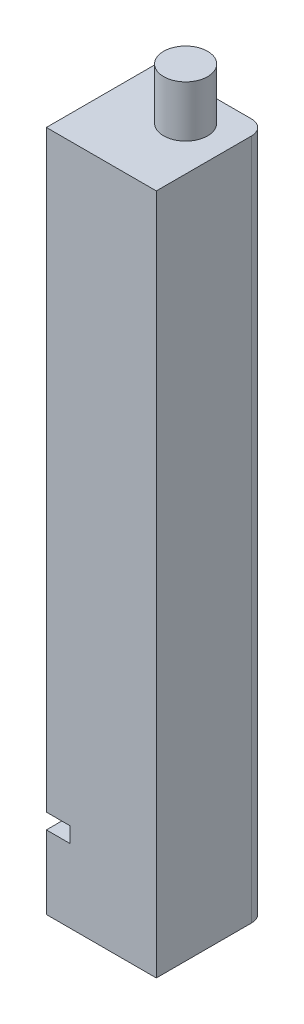
SolidWorks part; units mm, degrees
ref_plane "Front Plane" through (0, 0, 0) normal (0, 0, 1) x (1, 0, 0)
ref_plane "Top Plane" through (0, 0, 0) normal (0, 1, 0) x (1, 0, 0)
ref_plane "Right Plane" through (0, 0, 0) normal (1, 0, 0) x (0, 0, -1)
sketch "Sketch1" plane through (0, 0, 0) normal (0, 1, 0) x (1, 0, 0)
  line L0 (-68.486, 0) -> (57.6746, 0) construction
  line L1 (0, 62.7099) -> (0, -58.019) construction
  line L3 (-7.5, -7.5) -> (7.5, -7.5)
  line L4 (-7.5, -7.5) -> (-7.5, 7.5)
  line L5 (-7.5, 7.5) -> (7.5, 7.5)
  line L6 (7.5, -7.5) -> (7.5, 7.5)
  line L7 (-7.5, -7.5) -> (7.5, 7.5) construction
  line L8 (-7.5, 7.5) -> (7.5, -7.5) construction
  point P5 (0, 0)
  dimension "D1" = 15
  dimension "D2" = 15
extrude "Boss-Extrude1" add sketch "Sketch1" along normal blind 93
sketch "Sketch2" plane through (0, 93, 0) normal (0, 1, 0) x (1, 0, 0)
  line L0 (7.5, -7.5) -> (7.5, 7.5) construction
  line L2 (7.5, 7.5) -> (-7.5, 7.5) construction
  circle A0 centre (1.5, 2.5) radius 3
  dimension "D1" = 6
  dimension "D2" = 6
  dimension "D3" = 5
extrude "Boss-Extrude2" add sketch "Sketch2" along normal blind 7
sketch "Sketch3" plane through (0, 0, 7.5) normal (0, 0, 1) x (1, 0, 0)
  line L0 (-7.5, 12.1) -> (-4.3, 12.1)
  line L1 (-7.5, 93) -> (-7.5, 0) construction
  line L2 (-4.3, 12.1) -> (-4.3, 10)
  line L3 (-4.3, 10) -> (-7.5, 10)
  line L4 (-7.5, 10) -> (-7.5, 12.1)
  dimension "D1" = 10
  dimension "D2" = 2.1
  dimension "D3" = 3.2
extrude "Cut-Extrude1" cut sketch "Sketch3" against normal through all
fillet "Fillet1" radius 2 1 edges at (7.5, 46.5, -7.5)
